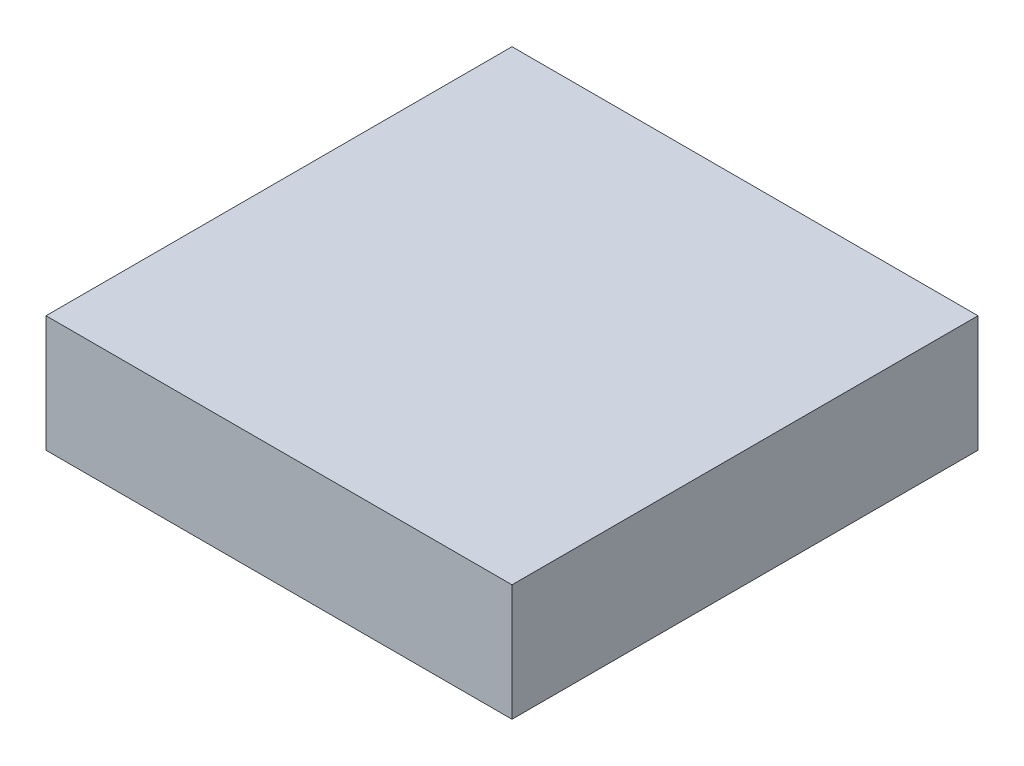
SolidWorks part; units mm, degrees
ref_plane "Front Plane" through (0, 0, 0) normal (0, 0, 1) x (1, 0, 0)
ref_plane "Top Plane" through (0, 0, 0) normal (0, 1, 0) x (1, 0, 0)
ref_plane "Right Plane" through (0, 0, 0) normal (1, 0, 0) x (0, 0, -1)
sketch "Sketch2" plane through (0, 0, 0) normal (0, 1, 0) x (1, 0, 0)
  line L1 (-101.6, 101.6) -> (101.6, 101.6)
  line L2 (-101.6, 101.6) -> (-101.6, -101.6)
  line L3 (-101.6, -101.6) -> (101.6, -101.6)
  line L4 (101.6, 101.6) -> (101.6, -101.6)
  line L5 (-101.6, 101.6) -> (101.6, -101.6) construction
  line L6 (-101.6, -101.6) -> (101.6, 101.6) construction
  point P0 (0, 0)
  dimension "D1" = 203.2
  dimension "D2" = 203.2
extrude "Boss-Extrude1" add sketch "Sketch2" along normal blind 50.8 contours L2 L3 L4 L1
sketch "Sketch3" plane through (0, 50.8, 0) normal (0, 1, 0) x (1, 0, 0)
  circle A0 centre (12.7, -12.7) radius 0.6452
  point P2 (0, 0)
  dimension "D3" = 1.2903
  dimension "D1" = 12.7
  dimension "D2" = 12.7
